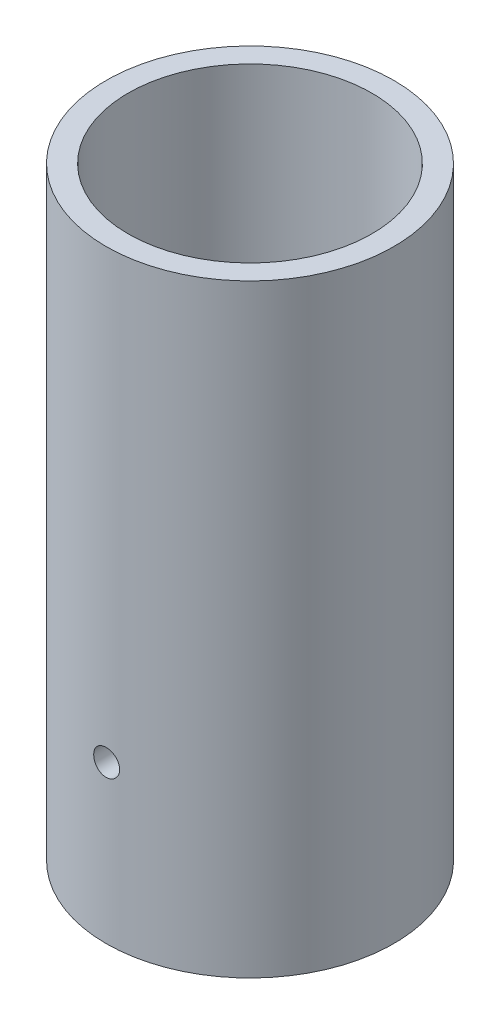
SolidWorks part; units mm, degrees
ref_plane "Front" through (0, 0, 0) normal (0, 0, 1) x (1, 0, 0)
ref_plane "Top" through (0, 0, 0) normal (0, 1, 0) x (1, 0, 0)
ref_plane "Right" through (0, 0, 0) normal (1, 0, 0) x (0, 0, -1)
sketch "Sketch1" plane through (0, 0, 0) normal (0, 1, 0) x (1, 0, 0)
  circle A0 centre (0, 0) radius 30.275
  circle A1 centre (0, 0) radius 25.65
  dimension "D1" = 51.3
  dimension "D2" = 60.55
extrude "Boss-Extrude1" add sketch "Sketch1" along normal blind 127
sketch "Sketch2" plane through (0, 0, 0) normal (0, 0, 1) x (1, 0, 0)
  circle A0 centre (0, 33.02) radius 2.7305
  dimension "D1" = 5.461
  dimension "1.3 IN" = 33.02
extrude "Cut-Extrude1" cut sketch "Sketch2" against normal through all both and the other way through all
